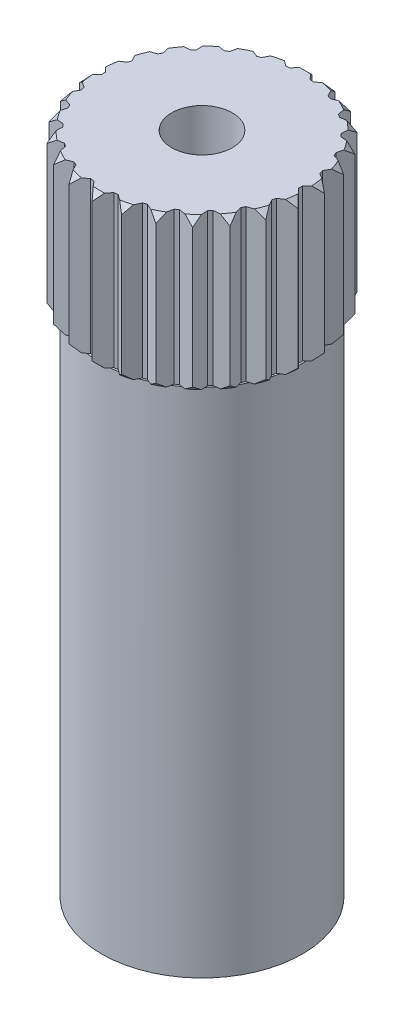
SolidWorks part; units mm, degrees
material "Brass"
ref_plane "Front Plane" through (0, 0, 0) normal (0, 0, 1) x (1, 0, 0)
ref_plane "Top Plane" through (0, 0, 0) normal (0, 1, 0) x (1, 0, 0)
ref_plane "Right Plane" through (0, 0, 0) normal (1, 0, 0) x (0, 0, -1)
sketch "Sketch12" plane through (0, 0, 0) normal (0, 1, 0) x (1, 0, 0)
  circle A0 centre (0, 0) radius 2.9
  dimension "D1" = 5.8
extrude "Boss-Extrude4" add sketch "Sketch12" along normal blind 13.5 separate body
sketch "Sketch13" plane through (0, 13.5, 0) normal (0, 1, 0) x (1, 0, 0)
  circle A2 centre (0, 0) radius 2.6
  circle A3 centre (0, 0) radius 2.9 construction
  dimension "D1" = 0.3
extrude "Boss-Extrude5" add sketch "Sketch13" along normal blind 4
sketch "Sketch14" plane through (0, 17.5, 0) normal (0, 1, 0) x (1, 0, 0)
  line L0 (0, 2.6) -> (0, 2.9) construction
  line L1 (0, 2.9) -> (-0.2629, 2.5867)
  line L2 (0, 2.9) -> (0.2629, 2.5867)
  line L3 (-0.2629, 2.5867) -> (0.2629, 2.5867) construction
  circle A0 centre (0, 0) radius 2.9 construction
  circle A1 centre (0, 0) radius 2.6
  arc A2 (0.2629, 2.5867) -> (-0.2629, 2.5867) centre (0, 0) ccw
  dimension "D2" = 80
  dimension "D3" = 0.5258
  dimension "D4" = 0.3
  dimension "D1" = 0
extrude "Boss-Extrude6" add sketch "Sketch14" against normal up to body
pattern_circular "CirPattern1" count 26 over 360 about axis through (0, 0, 0) along (0, 1, 0) of "Boss-Extrude6"
sketch "Sketch15" plane through (0, 0, 0) normal (1, 0, 0) x (0, 0, -1)
  line L0 (2.9, 17.3232) -> (2.9, 17.5)
  line L1 (2.9, 13.5) -> (2.9, 17.5) construction
  line L2 (2.9, 17.5) -> (2.7232, 17.5)
  line L3 (2.1682, 17.5) -> (2.5678, 17.5) construction
  line L4 (2.7232, 17.5) -> (2.9, 17.3232)
  dimension "D1" = 45
  dimension "D2" = 0.25
revolve "Cut-Revolve1" cut sketch "Sketch15" angle 360 about axis through (0, 17.5, 0) along (0, -1, 0)
sketch "Sketch16" plane through (0, 17.5, 0) normal (0, 1, 0) x (1, 0, 0)
  circle A0 centre (0, 0) radius 0.8
  dimension "D1" = 1.6
extrude "Cut-Extrude1" cut sketch "Sketch16" against normal blind 4
ref_plane "Plane1" through (-0.3638, 13.5, -2.5744) normal (-0.9902, 0, 0.1399) x (0.1399, 0, 0.9902)
sketch "Sketch17" plane through (0, 0, 0) normal (0, 0, 1) x (1, 0, 0)
  line L0 (2.9, 0) -> (2.65, 0)
  line L1 (-2.9, 0) -> (2.9, 0) construction
  line L2 (2.65, 0) -> (2.65, 13.5)
  line L3 (2.65, 13.5) -> (2.9, 13.5)
  line L4 (2.9, 13.5) -> (2.9, 0)
  line L5 (0, 0) -> (2.65, 0) construction
  line L6 (2.7115, 13.5) -> (2.3254, 13.5) construction
  dimension "D1" = 0.25
  dimension "D2" = 2.65
  dimension "D3" = 2.9
revolve "Cut-Revolve2" cut sketch "Sketch17" angle 360 about axis through (0, 13.5, 0) along (0, -1, 0)
ref_plane "Plane2" through (0, 15.5, 0) normal (0, 1, 0) x (1, 0, 0)
mirror "Mirror1" about plane through (0, 15.5, 0) normal (0, 1, 0) of "Cut-Revolve1"
